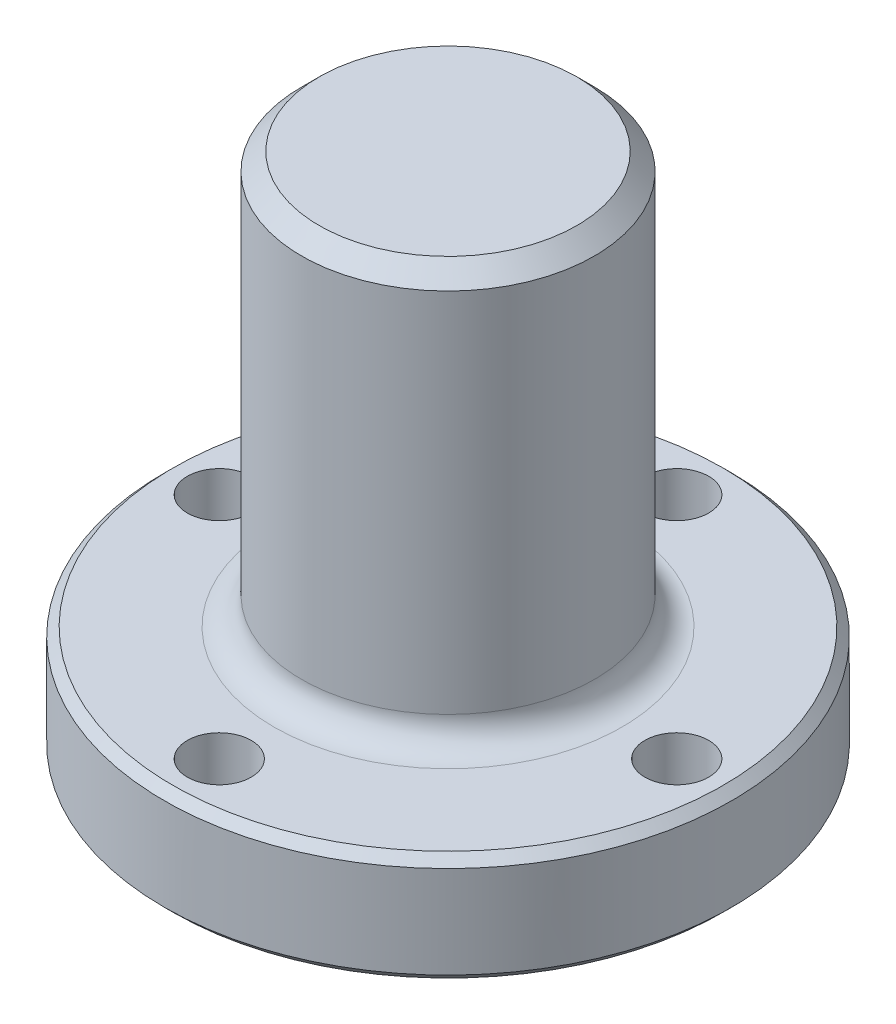
SolidWorks part; units mm, degrees
ref_plane "Front Plane" through (0, 0, 0) normal (1, 0, 0) x (0, 1, 0)
ref_plane "Top Plane" through (0, 0, 0) normal (0, 0, 1) x (0, 1, 0)
ref_plane "Right Plane" through (0, 0, 0) normal (0, 1, 0) x (-1, 0, 0)
sketch "Sketch1" plane through (0, 0, 0) normal (0, 0, 1) x (0, 1, 0)
  line L0 (-25.0317, 0) -> (-25.0317, 8.7122)
  line L1 (-25.0317, 8.7122) -> (-20.2057, 8.7122)
  line L2 (-20.2057, 8.7122) -> (-20.2057, 24.6126)
  line L3 (-20.2057, 24.6126) -> (-10.6807, 24.6126)
  line L4 (-10.6807, 24.6126) -> (-10.6807, 12.7)
  line L5 (-10.6807, 12.7) -> (25.0317, 12.7)
  line L6 (25.0317, 12.7) -> (25.0317, 0)
  line L7 (25.0317, 0) -> (-25.0317, 0)
  line L8 (-50.4317, 0) -> (50.4317, 0) construction
revolve "Revolve1" add sketch "Sketch1" angle 360 about L8
fillet "Fillet1" radius 2.3876 1 edges at (0, -10.6807, -12.7)
chamfer "Chamfer1" distance 0.762 angle 45 3 edges at (0, -10.6807, -24.6126) (0, -20.2057, -24.6126) (0, -25.0317, -8.7122)
chamfer "Chamfer2" distance 1.524 angle 45 1 edges at (0, 25.0317, -12.7)
sketch "Sketch2" plane through (0, 0, 0) normal (0, 1, 0) x (-1, 0, 0)
  circle A0 centre (19.8374, 0) radius 2.7686
extrude "Cut-Extrude2" cut sketch "Sketch2" against normal blind 10.6807 from offset 10.6807
sketch "Sketch3" plane through (0, 0, 0) normal (0, 1, 0) x (-1, 0, 0)
  circle A0 centre (0, 19.8374) radius 2.7686
  circle A1 centre (-19.8374, 0) radius 2.7686
  circle A2 centre (0, -19.8374) radius 2.7686
extrude "Cut-Extrude4" cut sketch "Sketch3" against normal blind 10.6807 from offset 10.6807
